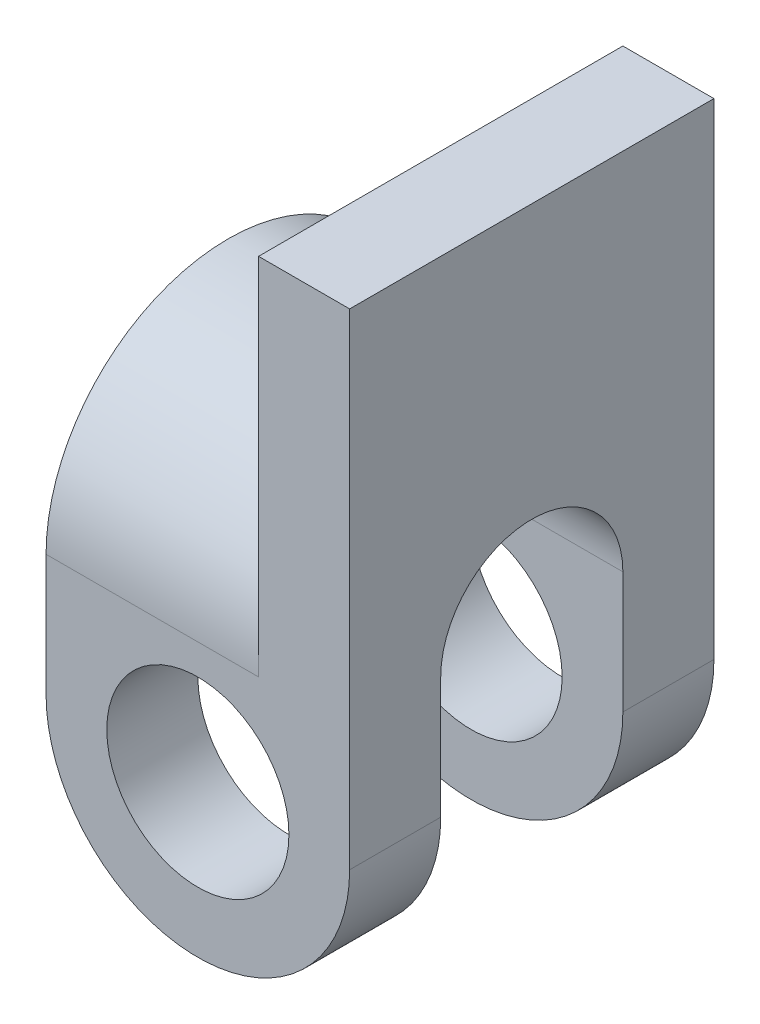
SolidWorks part; units mm, degrees
ref_plane "Front Plane" through (0, 0, 0) normal (0, 0, 1) x (1, 0, 0)
ref_plane "Top Plane" through (0, 0, 0) normal (0, 1, 0) x (1, 0, 0)
ref_plane "Right Plane" through (0, 0, 0) normal (1, 0, 0) x (0, 0, -1)
sketch "Sketch1" plane through (0, 0, 0) normal (0, 0, 1) x (1, 0, 0)
  line L0 (25, 0) -> (25, 80)
  line L1 (25, 80) -> (10, 80)
  line L2 (10, 80) -> (10, 20)
  line L3 (-25, 20) -> (10, 20)
  line L4 (-25, 20) -> (-25, 0)
  arc A0 (-25, 0) -> (25, 0) centre (0, 0) ccw
  circle A1 centre (0, 0) radius 15
  dimension "D1" = 50
  dimension "D2" = 30
  dimension "D3" = 80
  dimension "D4" = 15
  dimension "D5" = 20
  dimension "D6" = 35
extrude "Boss-Extrude1" add sketch "Sketch1" along normal blind 60
sketch "Sketch2" plane through (-25, 0, 0) normal (-1, 0, 0) x (0, 0, 1)
  line L0 (60, 20) -> (0, 20) construction
  line L1 (15, 20) -> (0, 20)
  line L2 (45, 20) -> (60, 20)
  arc A0 (45, 20) -> (15, 20) centre (30, 20) ccw
  arc A1 (60, 20) -> (0, 20) centre (30, 20) ccw
  dimension "D1" = 60
  dimension "D2" = 30
extrude "Boss-Extrude2" add sketch "Sketch2" against normal up to surface (35 mm away) up to face at (10, 50, 30)
sketch "Sketch4" plane through (-25, 0, 0) normal (-1, 0, 0) x (0, 0, 1)
  line L0 (45, 20) -> (15, 20) construction
  line L1 (15, 20) -> (15, -31.3863)
  line L2 (45, 20) -> (45, -31.3863)
  line L3 (15, -31.3863) -> (45, -31.3863)
  arc A0 (45, 20) -> (15, 20) centre (30, 20) ccw
extrude "Cut-Extrude9" cut sketch "Sketch4" against normal blind 68
